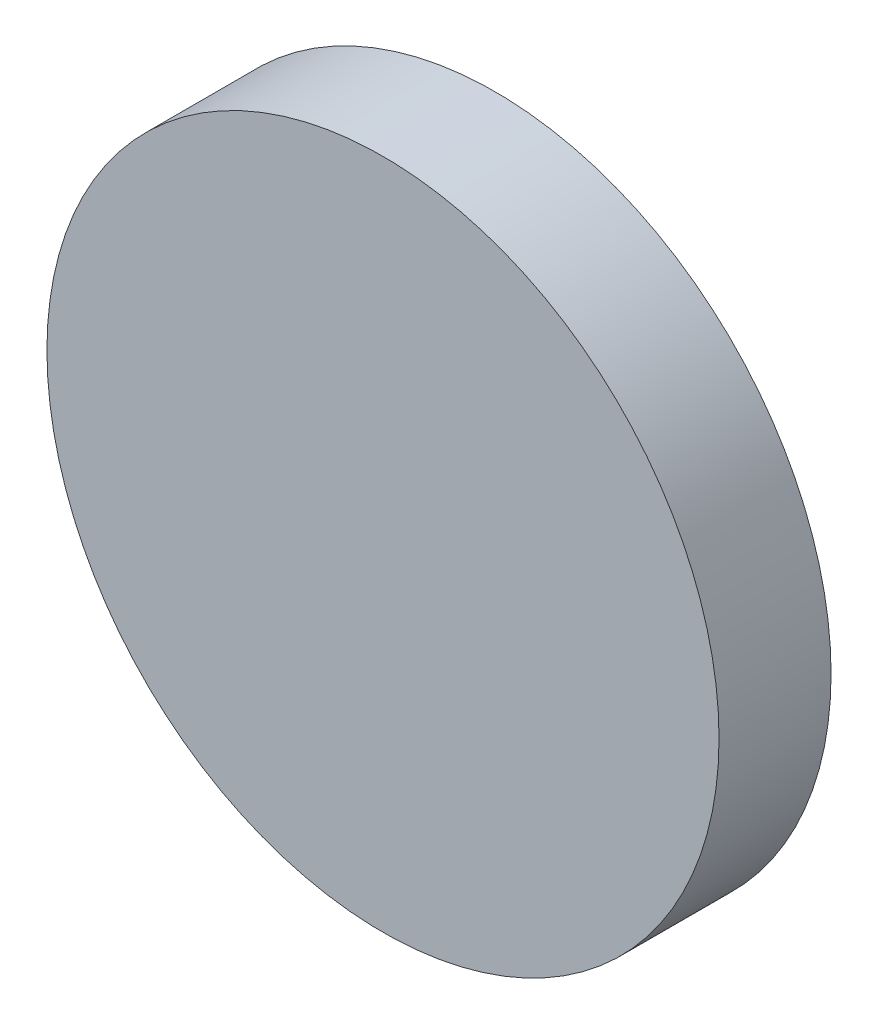
SolidWorks part; units mm, degrees
ref_plane "Front Plane" through (0, 0, 0) normal (0, 0, 1) x (1, 0, 0)
ref_plane "Top Plane" through (0, 0, 0) normal (0, 1, 0) x (1, 0, 0)
ref_plane "Right Plane" through (0, 0, 0) normal (1, 0, 0) x (0, 0, -1)
sketch "Sketch1" plane through (0, 0, 0) normal (0, 0, 1) x (1, 0, 0)
  circle A0 centre (0, 0) radius 19.05
  dimension "D1" = 38.1
extrude "Boss-Extrude1" add sketch "Sketch1" along normal blind 6.35
